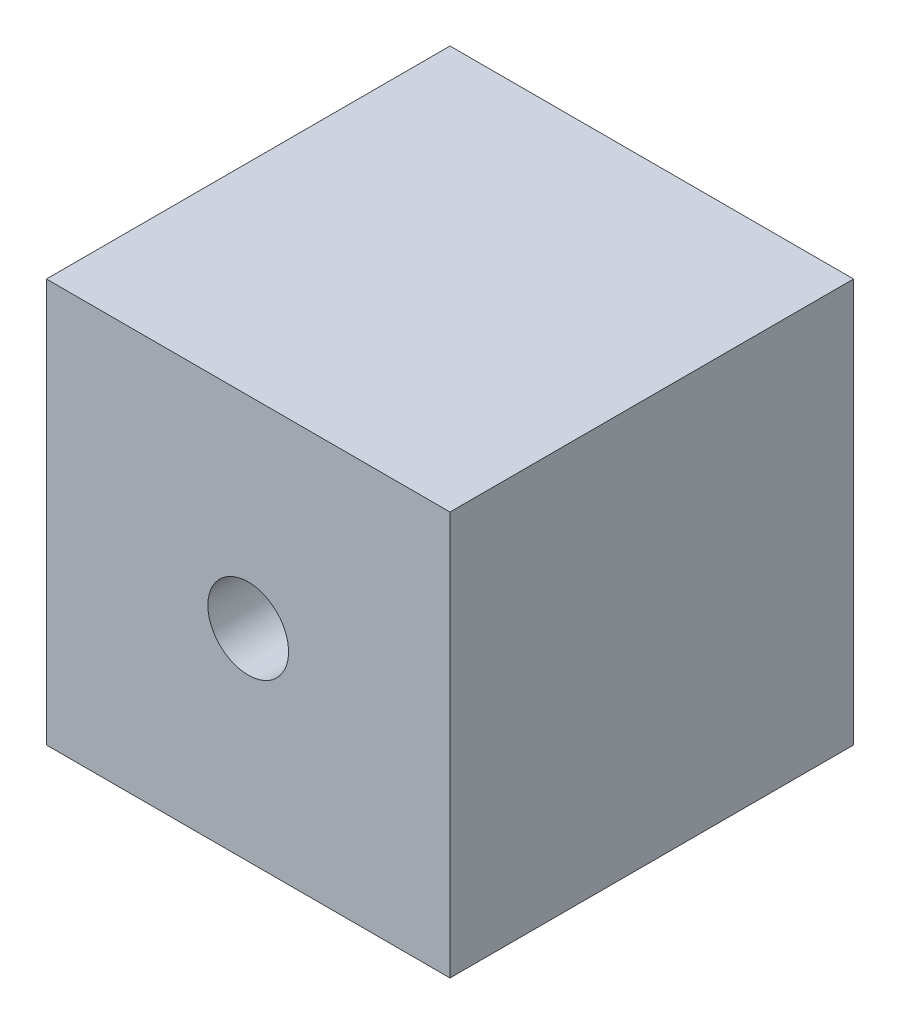
SolidWorks part; units mm, degrees
ref_plane "Front Plane" through (0, 0, 0) normal (0, 0, 1) x (1, 0, 0)
ref_plane "Top Plane" through (0, 0, 0) normal (0, 1, 0) x (1, 0, 0)
ref_plane "Right Plane" through (0, 0, 0) normal (1, 0, 0) x (0, 0, -1)
sketch "Test_box_Profile" plane through (0, 0, 0) normal (0, 0, 1) x (1, 0, 0)
  line L1 (-10, -10) -> (10, -10)
  line L2 (-10, -10) -> (-10, 10)
  line L3 (-10, 10) -> (10, 10)
  line L4 (10, -10) -> (10, 10)
extrude "Test_box" add sketch "Test_box_Profile" along normal blind 20 from offset 10
sketch "Test_cut_Profile" plane through (0, 0, 0) normal (0, 0, 1) x (1, 0, 0)
  circle A0 centre (0, 0) radius 2
extrude "Test_cut" cut sketch "Test_cut_Profile" along normal blind 24 from offset 12
